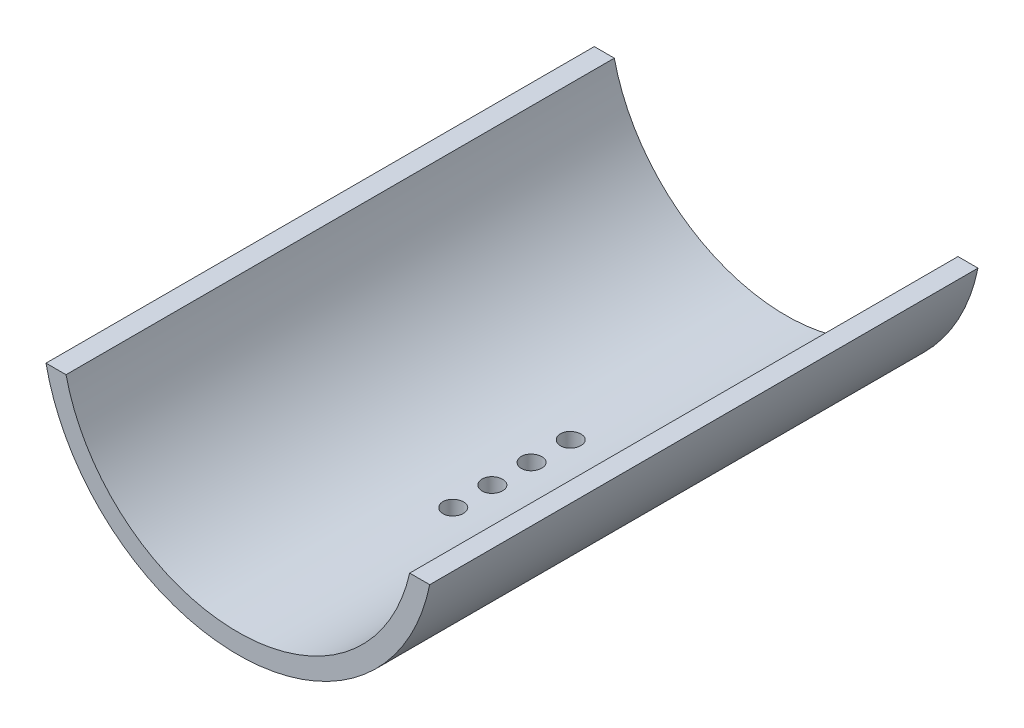
SolidWorks part; units mm, degrees
material "Polyurethane Foam Flexible"
ref_plane "Front Plane" through (0, 0, 0) normal (0, 0, 1) x (1, 0, 0)
ref_plane "Top Plane" through (0, 0, 0) normal (0, 1, 0) x (1, 0, 0)
ref_plane "Right Plane" through (0, 0, 0) normal (1, 0, 0) x (0, 0, -1)
sketch "Sketch2" plane through (0, 0, 0) normal (0, -1, 0) x (0, 0, -1)
  line L0 (0, 0) -> (-66.4006, 0) construction
  line L1 (-28.3687, -63.5) -> (149.4313, -63.5)
  line L2 (-28.3687, -63.5) -> (-28.3687, -57.15)
  line L3 (-28.3687, -57.15) -> (149.4313, -57.15)
  line L4 (149.4313, -63.5) -> (149.4313, -57.15)
  line L5 (-28.3687, -63.5) -> (149.4313, -57.15) construction
  line L6 (-28.3687, -57.15) -> (149.4313, -63.5) construction
  point P0 (60.5313, -60.325)
  dimension "D1" = 6.35
  dimension "D2" = 63.5
  dimension "D3" = 177.8
revolve "Revolve1" add sketch "Sketch2" angle 180 about L0
sketch "Sketch3" plane through (0, 0, 0) normal (0, 1, 0) x (1, 0, 0)
  line L0 (0, 66.8813) -> (0, 54.1813) construction
  line L1 (-57.15, 149.4313) -> (-57.15, -28.3687) construction
  circle A0 centre (0, 66.8813) radius 3.3275
  circle A1 centre (0, 54.1813) radius 3.3275
  circle A2 centre (0, 79.5813) radius 3.3275
  circle A3 centre (0, 41.4813) radius 3.3275
  point P5 (-57.15, 60.5313)
  point P10 (0, 60.5313)
  dimension "D1" = 6.655
  dimension "D3" = 12.7
  dimension "D2" = 12.7
  dimension "D4" = 12.7
extrude "Cut-Extrude1" cut sketch "Sketch3" against normal through all
sketch "Sketch4" plane through (0, 0, 28.3687) normal (0, 0, 1) x (1, 0, 0)
  line L0 (-81.5672, -12.7) -> (81.5672, -12.7)
  line L2 (0, 0) -> (0, 45.2299) construction
  arc A0 (81.5672, -12.7) -> (-81.5672, -12.7) centre (0, 0) ccw
  arc A2 (-63.5, 0) -> (63.5, 0) centre (0, 0) ccw construction
  point P1 (0, -63.5)
  point P2 (0, 0)
  point P6 (0, 0)
  point P12 (0, 0)
  dimension "D1" = 82.55
  dimension "D2" = 50.8
extrude "Cut-Extrude2" cut sketch "Sketch4" against normal through all
